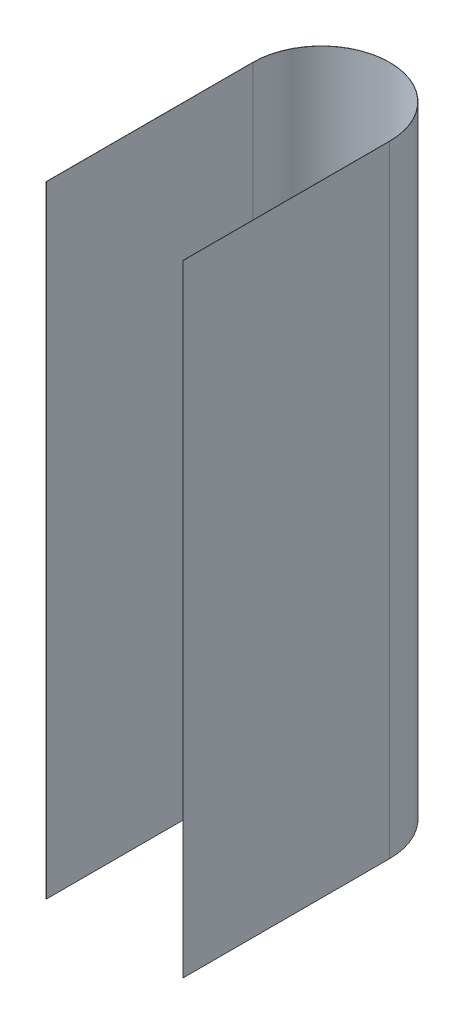
SolidWorks part; units mm, degrees
ref_plane "Front Plane" through (0, 0, 0) normal (0, 0, 1) x (1, 0, 0)
ref_plane "Top Plane" through (0, 0, 0) normal (0, 1, 0) x (1, 0, 0)
ref_plane "Right Plane" through (0, 0, 0) normal (1, 0, 0) x (0, 0, -1)
sketch "Sketch1" plane through (0, 0, 0) normal (0, 1, 0) x (1, 0, 0)
  line L0 (0, 0) -> (0, -100)
  line L1 (66, 0) -> (66, -100)
  line L2 (-0.1, 0) -> (-0.1, -100)
  line L3 (-0.1, -100) -> (0, -100)
  line L4 (66.1, 0) -> (66.1, -100)
  line L5 (66.1, -100) -> (66, -100)
  arc A0 (0, 0) -> (66, 0) centre (33, 0) cw
  arc A1 (-0.1, 0) -> (66.1, 0) centre (33, 0) cw
  dimension "D2" = 100
  dimension "D4" = 0.1
  dimension "D1" = 66
  dimension "D3" = 100
extrude "Boss-Extrude1" add sketch "Sketch1" along normal blind 300.5
